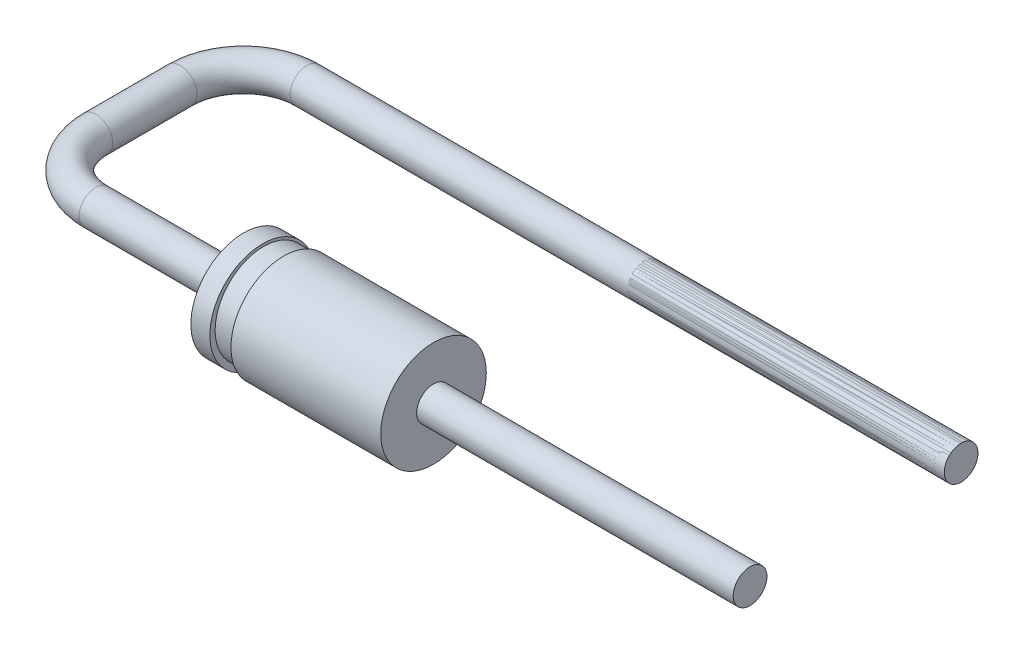
SolidWorks part; units mm, degrees
ref_plane "Front" through (0, 0, 0) normal (0, 0, 1) x (1, 0, 0)
ref_plane "Top" through (0, 0, 0) normal (0, 1, 0) x (1, 0, 0)
ref_plane "Right" through (0, 0, 0) normal (1, 0, 0) x (0, 0, -1)
ref_plane "Плоскость1" through (2.95, 0, 0) normal (1, 0, 0) x (0, 0, -1)
sketch "Эскиз3" plane through (2.95, 0, 0) normal (1, 0, 0) x (0, 0, -1)
  circle A0 centre (-1.525, -0.0336) radius 1.25
  dimension "D2" = 2.5
  dimension "D1" = 1.525
extrude "Вытянуть1" add sketch "Эскиз3" along normal blind 4.5
sketch "Эскиз4" plane through (0, 0, 0) normal (0, 1, 0) x (1, 0, 0)
  line L0 (0, -1.5) -> (10.3423, -1.5) construction
  line L3 (3.4, 0.15) -> (3.9, 0.15)
  line L4 (3.4, 0.15) -> (3.4, -0.35)
  line L5 (3.4, -0.35) -> (3.9, -0.35)
  line L6 (3.9, 0.15) -> (3.9, -0.35)
  dimension "D1" = 1.5
  dimension "D2" = 3.4
  dimension "D3" = 0.5
  dimension "D4" = 0.5
  dimension "D5" = 0.35
revolve "Вырез-Повернуть1" cut sketch "Эскиз4" angle 360 about L0
sketch "Эскиз7" plane through (7.45, 0, 0) normal (1, 0, 0) x (0, 0, -1)
  circle A0 centre (-1.525, -0.0336) radius 0.4
  circle A1 centre (-1.525, -0.0336) radius 1.25 construction
  dimension "D1" = 0.8
extrude "Вытянуть3" add sketch "Эскиз7" along normal blind 7.5
sketch "Эскиз8" plane through (0, 0, 0) normal (0, 1, 0) x (1, 0, 0)
  line L0 (2.95, -1.525) -> (-0.55, -1.525)
  line L1 (2.95, -0.275) -> (2.95, -2.775) construction
  line L2 (-2.05, -0.025) -> (-2.05, 1.975)
  line L3 (-0.55, 3.475) -> (14.95, 3.475)
  line L5 (14.95, -1.925) -> (14.95, -1.125) construction
  arc A0 (-2.05, 1.975) -> (-0.55, 3.475) centre (-0.55, 1.975) cw
  arc A1 (-0.55, -1.525) -> (-2.05, -0.025) centre (-0.55, -0.025) cw
  dimension "D3" = 1.5
  dimension "D1" = 5
  dimension "D2" = 5
sketch "Эскиз9" plane through (14.95, 0, 0) normal (1, 0, 0) x (0, 0, -1)
  line L0 (3.475, 0) -> (1.975, 0) construction
  circle A0 centre (3.475, 0) radius 0.4
  circle A1 centre (-1.525, -0.0336) radius 0.4 construction
surface "Поверхность-По траектории2"
sketch "Эскиз10" plane through (14.95, 0, 0) normal (1, 0, 0) x (0, 0, -1)
  circle A0 centre (3.475, 0) radius 0.4 construction
  circle A1 centre (3.475, 0) radius 0.4
extrude "Вытянуть4" add sketch "Эскиз10" against normal blind 7.5
